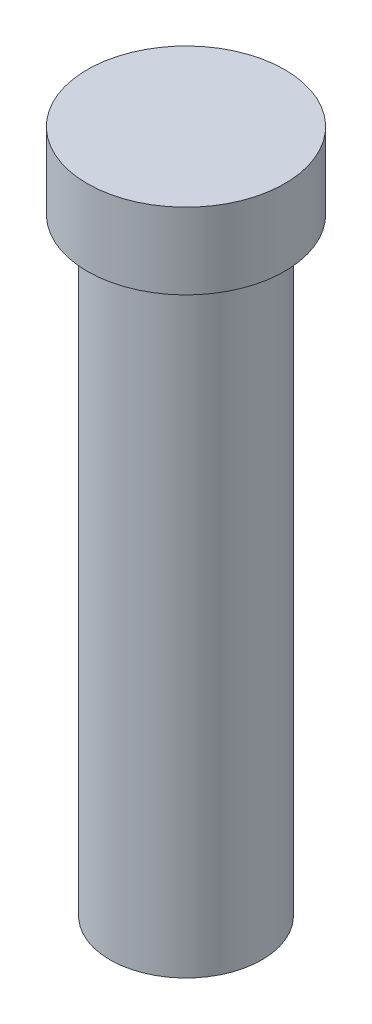
SolidWorks part; units mm, degrees
material "1.2316 (X36CrMo17)"
ref_plane "Front Plane" through (0, 0, 0) normal (0, 0, 1) x (1, 0, 0)
ref_plane "Top Plane" through (0, 0, 0) normal (0, 1, 0) x (1, 0, 0)
ref_plane "Right Plane" through (0, 0, 0) normal (1, 0, 0) x (0, 0, -1)
sketch "Sketch1" plane through (0, 0, 0) normal (0, 0, 1) x (1, 0, 0)
  line L0 (0, 0) -> (6.5, 0)
  line L1 (6.5, 0) -> (6.5, -5)
  line L2 (6.5, -5) -> (5, -5)
  line L3 (5, -5) -> (5, -45)
  line L4 (5, -45) -> (0, -45)
  line L5 (0, -45) -> (0, 0)
  line L6 (0, 8.477) -> (0, -63.2688) construction
  dimension "D1" = 13
  dimension "D2" = 10
  dimension "D3" = 5
  dimension "D4" = 45
revolve "Revolve1" add sketch "Sketch1" angle 360 about L6
